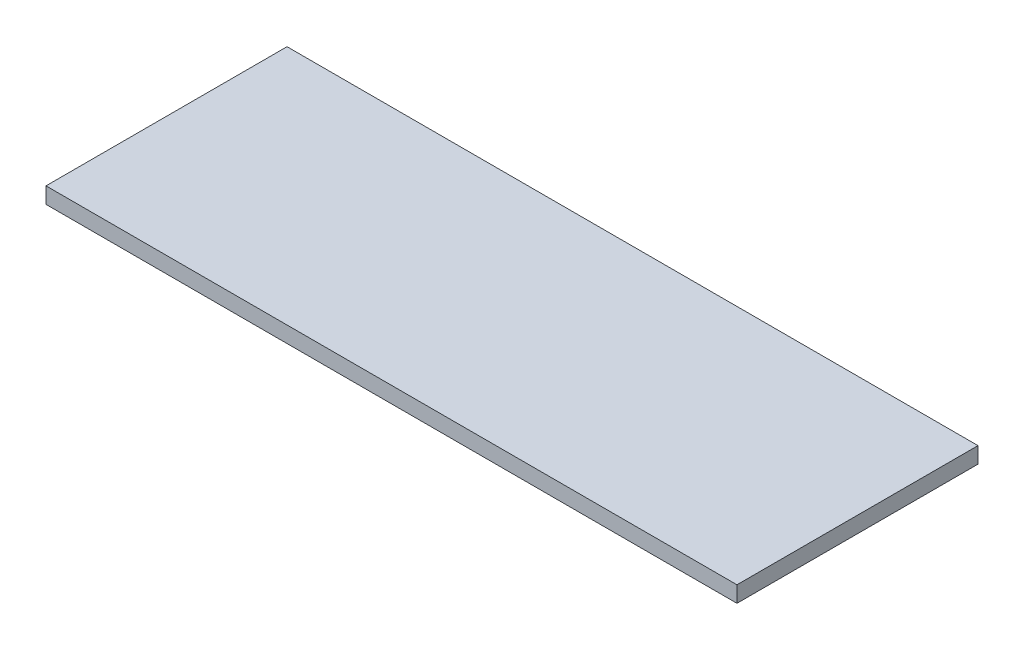
SolidWorks part; units mm, degrees
ref_plane "Front Plane" through (0, 0, 0) normal (0, 0, 1) x (1, 0, 0)
ref_plane "Top Plane" through (0, 0, 0) normal (0, 1, 0) x (1, 0, 0)
ref_plane "Right Plane" through (0, 0, 0) normal (1, 0, 0) x (0, 0, -1)
sketch "Sketch1" plane through (0, 0, 0) normal (0, 1, 0) x (1, 0, 0)
  line L1 (-215, -75) -> (215, -75)
  line L2 (-215, -75) -> (-215, 75)
  line L3 (-215, 75) -> (215, 75)
  line L4 (215, -75) -> (215, 75)
  line L5 (-215, -75) -> (215, 75) construction
  line L6 (-215, 75) -> (215, -75) construction
  point P0 (0, 0)
  dimension "D1" = 150
  dimension "D2" = 430
extrude "Boss-Extrude1" add sketch "Sketch1" along normal blind 10
